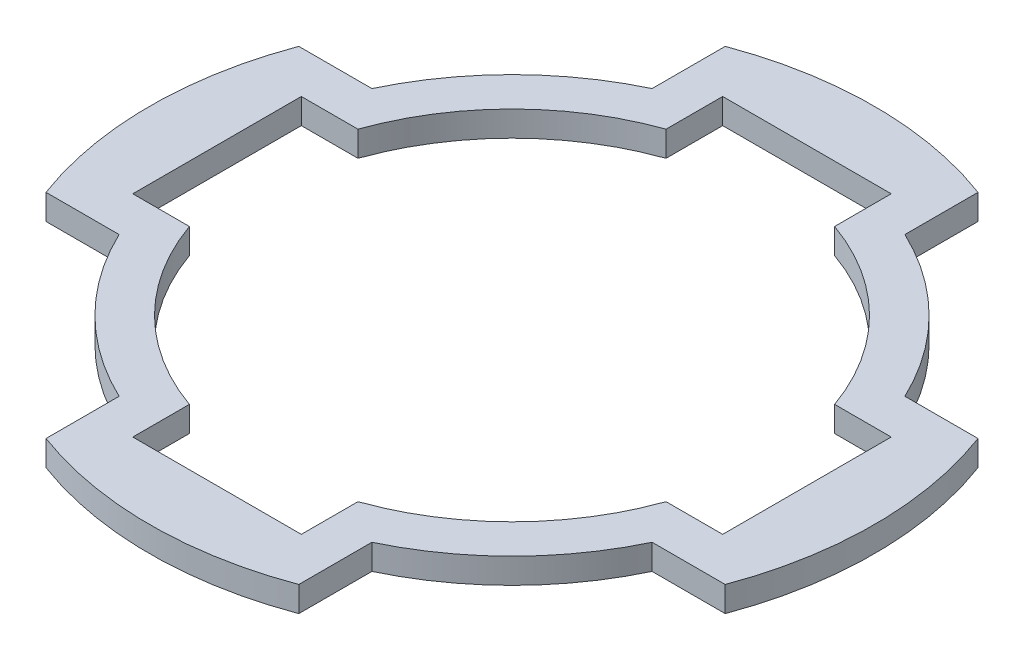
SolidWorks part; units mm, degrees
ref_plane "Front Plane" through (0, 0, 0) normal (0, 0, 1) x (1, 0, 0)
ref_plane "Top Plane" through (0, 0, 0) normal (0, 1, 0) x (1, 0, 0)
ref_plane "Right Plane" through (0, 0, 0) normal (1, 0, 0) x (0, 0, -1)
sketch "Sketch1" plane through (0, 0, 0) normal (0, 1, 0) x (1, 0, 0)
  line L0 (-4.0299, 1.5) -> (-3.1623, 1.5)
  line L1 (-4.0299, -1.5) -> (-3.1623, -1.5)
  line L2 (-1.5, 4.0299) -> (-1.5, 3.1623)
  line L3 (1.5, 4.0299) -> (1.5, 3.1623)
  line L4 (-1.5, -3.1623) -> (-1.5, -4.0299)
  line L5 (1.5, -3.1623) -> (1.5, -4.0299)
  line L6 (3.1623, 1.5) -> (4.0299, 1.5)
  line L7 (3.1623, -1.5) -> (4.0299, -1.5)
  line L8 (-3.5, 1) -> (-2.8284, 1)
  line L9 (-3.5, 1) -> (-3.5, -1)
  line L10 (3.5, 1) -> (3.5, -1)
  line L11 (-3.5, -1) -> (-2.8284, -1)
  line L13 (2.8284, -1) -> (3.5, -1)
  line L14 (-1, -3.5) -> (1, -3.5)
  line L15 (-1, -2.8284) -> (-1, -3.5)
  line L16 (1, -2.8284) -> (1, -3.5)
  line L17 (2.8284, 1) -> (3.5, 1)
  line L18 (-1, 3.5) -> (1, 3.5)
  line L19 (1, 3.5) -> (1, 2.8284)
  line L20 (-1, 3.5) -> (-1, 2.8284)
  arc A0 (-3.1623, -1.5) -> (-1.5, -3.1623) centre (0, 0) ccw
  arc A2 (-2.8284, -1) -> (-1, -2.8284) centre (0, 0) ccw
  arc A3 (-4.0299, 1.5) -> (-4.0299, -1.5) centre (0, 0) ccw
  arc A4 (-1.5, -4.0299) -> (1.5, -4.0299) centre (0, 0) ccw
  arc A5 (4.0299, -1.5) -> (4.0299, 1.5) centre (0, 0) ccw
  arc A6 (1.5, 4.0299) -> (-1.5, 4.0299) centre (0, 0) ccw
  arc A7 (1.5, -3.1623) -> (3.1623, -1.5) centre (0, 0) ccw
  arc A8 (3.1623, 1.5) -> (1.5, 3.1623) centre (0, 0) ccw
  arc A9 (-1.5, 3.1623) -> (-3.1623, 1.5) centre (0, 0) ccw
  arc A10 (2.8284, 1) -> (1, 2.8284) centre (0, 0) ccw
  arc A11 (-1, 2.8284) -> (-2.8284, 1) centre (0, 0) ccw
  arc A12 (1, -2.8284) -> (2.8284, -1) centre (0, 0) ccw
  dimension "D1" = 7
  dimension "D2" = 6
  dimension "D7" = 8.6
  dimension "D3" = 1.5
  dimension "D4" = 1.5
  dimension "D5" = 1.5
  dimension "D6" = 1.5
  dimension "D8" = 180
  dimension "D9" = 3
  dimension "D10" = 0.8676
  dimension "D11" = 0.5
  dimension "D12" = 0.6716
  dimension "D13" = 90
  dimension "D14" = 0.5
  dimension "D15" = 0.6716
  dimension "D16" = 90
  dimension "D17" = 3.5
  dimension "D18" = 3.5
  dimension "D19" = 3.5
  dimension "D20" = 0.5
extrude "Boss-Extrude1" add sketch "Sketch1" along normal blind 0.3
